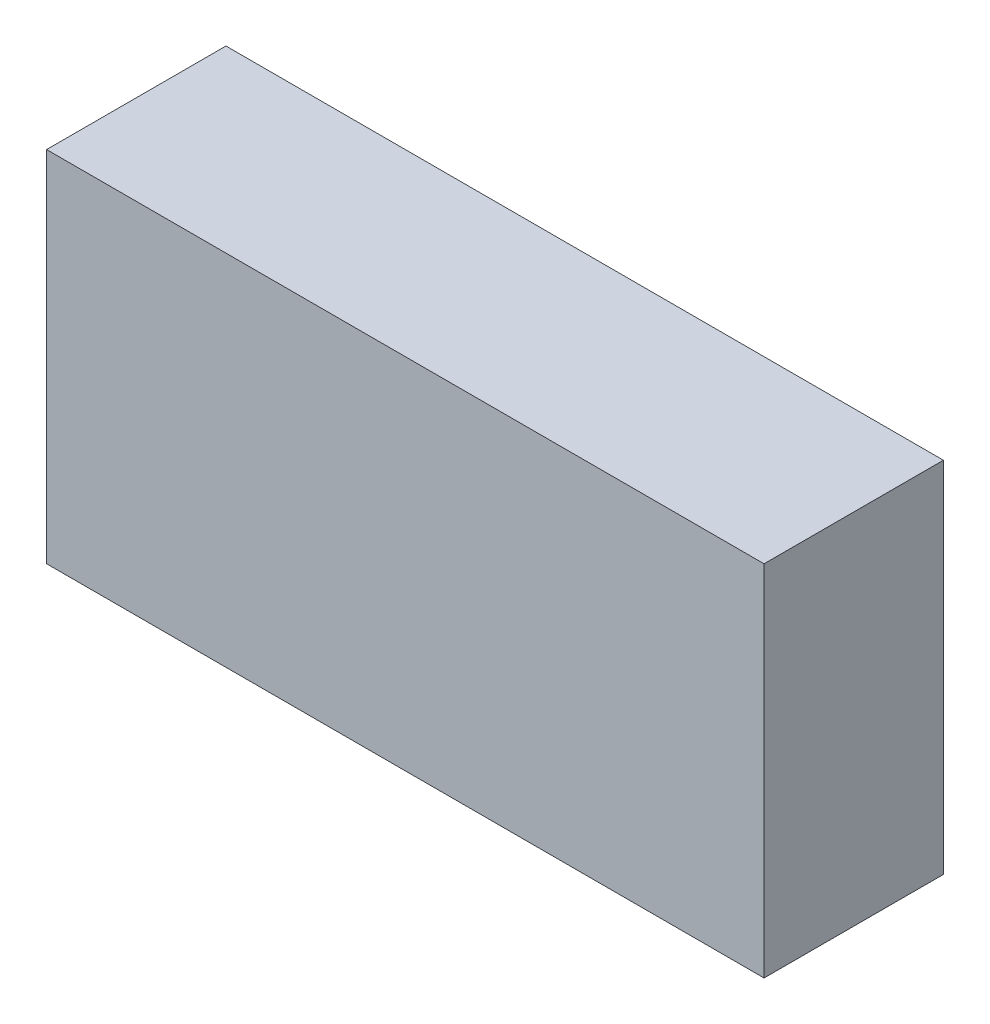
SolidWorks part; units mm, degrees
ref_plane "正面" through (0, 0, 0) normal (0, 0, 1) x (1, 0, 0)
ref_plane "平面" through (0, 0, 0) normal (0, 1, 0) x (1, 0, 0)
ref_plane "右側面" through (0, 0, 0) normal (1, 0, 0) x (0, 0, -1)
sketch "ｽｹｯﾁ1" plane through (0, 0, 0) normal (0, 0, 1) x (1, 0, 0)
  line L1 (0, 0) -> (200, 0)
  line L2 (0, 0) -> (0, 100)
  line L3 (0, 100) -> (200, 100)
  line L4 (200, 0) -> (200, 100)
extrude "ﾎﾞｽ - 押し出し1" add sketch "ｽｹｯﾁ1" along normal blind 50
